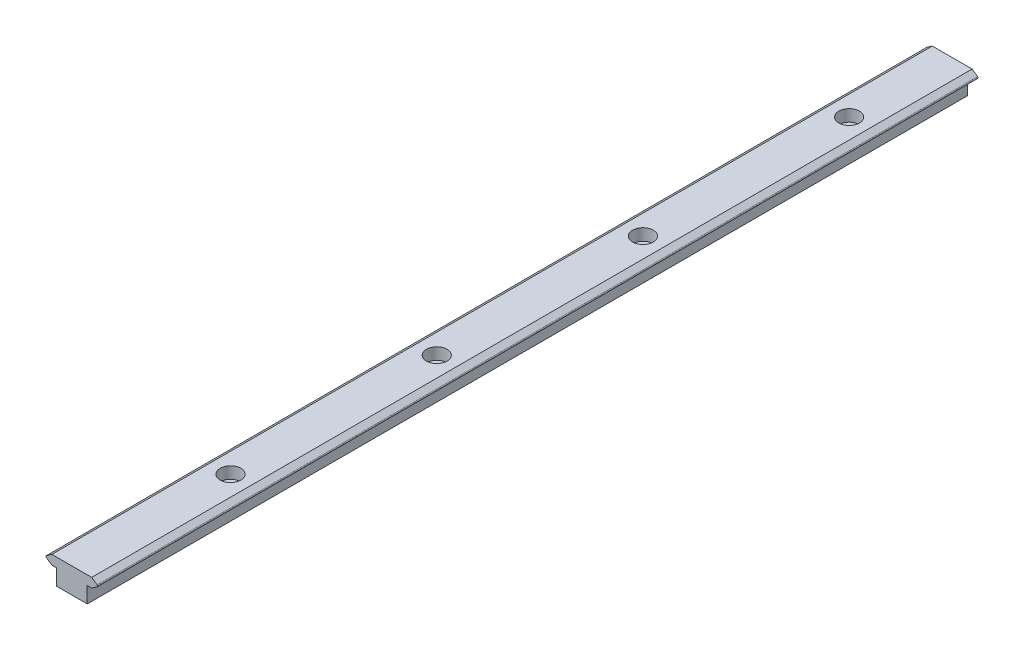
SolidWorks part; units mm, degrees
material "A6061"
ref_plane "前视基准面" through (0, 0, 0) normal (0, 0, 1) x (1, 0, 0)
ref_plane "上视基准面" through (0, 0, 0) normal (0, 1, 0) x (1, 0, 0)
ref_plane "右视基准面" through (0, 0, 0) normal (1, 0, 0) x (0, 0, -1)
sketch "草图1" plane through (0, 0, 0) normal (0, 0, 1) x (1, 0, 0)
  line L0 (185.1567, 2.25) -> (0, 2.25)
  line L1 (0, 2.25) -> (0, -2.25)
  line L2 (0, -2.25) -> (185.1567, -2.25)
  line L3 (185.1567, -2.25) -> (187.7851, -0.4096)
  line L4 (187.7851, 0.4096) -> (185.1567, 2.25)
  line L5 (0, 2.25) -> (0, -2.25) construction
  spline S0 degree 3 poles (187.7851, 0.4096) (187.8309, 0.3775) (187.8718, 0.337) (187.9045, 0.2916) (187.9371, 0.2461) (187.9623, 0.1944) (187.9781, 0.1407) (187.9938, 0.087) (188.0005, 0.0298) (187.9976, -0.0261) (187.9947, -0.082) (187.9821, -0.1381) (187.9608, -0.1899) (187.9396, -0.2417) (187.9091, -0.2905) (187.8719, -0.3323) (187.8461, -0.3612) (187.8168, -0.3874) (187.7851, -0.4096) knots 0 0 0 0 0.000168 0.000168 0.000168 0.000336 0.000336 0.000336 0.000504 0.000504 0.000504 0.000672 0.000672 0.000672 0.000839 0.000839 0.000839 0.000955 0.000955 0.000955 0.000955
revolve "旋转1" add sketch "草图1" angle 360 about L5
sketch "草图2" plane through (0, -2.25, 0) normal (0, -1, 0) x (1, 0, 0)
  circle A0 centre (0, 0) radius 183
extrude "凸台-拉伸1" add sketch "草图2" along normal blind 7.75
sketch "草图3" plane through (0, 0, 0) normal (0, 0, 1) x (1, 0, 0)
  line L0 (165.8433, 2.25) -> (0, 2.25)
  line L1 (0, 2.25) -> (0, -10)
  line L2 (0, -10) -> (168, -10)
  line L3 (168, -10) -> (168, -2.25)
  line L4 (168, -2.25) -> (165.8433, -2.25)
  line L5 (165.8433, -2.25) -> (163.2149, -0.4096)
  line L6 (163.2149, 0.4096) -> (165.8433, 2.25)
  line L7 (0, 2.25) -> (0, -10) construction
  arc A0 (163.2149, -0.4096) -> (163.2149, 0.4096) centre (163.5017, 0) cw
revolve "切除-旋转1" cut sketch "草图3" angle 360 about L7
hole_wizard "M5 六角头螺栓的柱形沉头孔1" positions "草图5" profile "草图4" counterbore size "M5" standard "ANSI Metric"
sketch "草图5" plane through (0, 2.25, 0) normal (0, 1, 0) x (1, 0, 0)
  point P0 (-45.4227, -169.52)
  point P1 (-124.0972, -124.0972)
  point P2 (-169.52, -45.4227)
  point P3 (45.4227, -169.52)
  point P4 (124.0972, -124.0972)
  point P5 (169.52, -45.4227)
  point P6 (-45.4227, 169.52)
  point P7 (-124.0972, 124.0972)
  point P8 (-169.52, 45.4227)
  point P9 (45.4227, 169.52)
  point P10 (124.0972, 124.0972)
  point P11 (169.52, 45.4227)
sketch "草图4" plane through (-45.4227, 2.25, 169.52) normal (1, 0, 0) x (0, 0, 1)
  line L0 (0, 0) -> (0, 12.25)
  line L1 (0, 12.25) -> (2.75, 12.25)
  line L3 (2.75, 12.25) -> (2.75, 6)
  line L4 (2.75, 6) -> (4.5, 6)
  line L5 (4.5, 6) -> (4.5, 0)
  line L7 (4.5, 0) -> (0, 0)
  line L11 (0, -6.35) -> (0, 107.95) construction
  dimension "通孔孔直径" = 5.5
  dimension "通孔孔深度" = 12.25
  dimension "柱形沉头孔直径" = 9
  dimension "柱形沉头孔深度" = 6
sketch "草图6" plane through (0, 2.25, 0) normal (0, 1, 0) x (1, 0, 0)
  line L1 (-255.1095, 0) -> (244.8021, 0)
  line L2 (-255.1095, 0) -> (-255.1095, -215.3522)
  line L3 (-255.1095, -215.3522) -> (244.8021, -215.3522)
  line L4 (244.8021, 0) -> (244.8021, -215.3522)
extrude "切除-拉伸1" cut sketch "草图6" against normal through all
sketch "草图7" plane through (0, 0, 0) normal (0, 0, 1) x (1, 0, 0)
  line L10 (-185.1567, 2.25) -> (-187.7851, 0.4096)
  line L11 (-187.7851, -0.4096) -> (-185.1567, -2.25)
  line L12 (-185.1567, -2.25) -> (-183, -2.25)
  line L13 (-183, -2.25) -> (-183, -10)
  line L14 (-183, -10) -> (-168, -10)
  line L15 (-168, -10) -> (-168, -2.25)
  line L16 (-168, -2.25) -> (-165.8433, -2.25)
  line L17 (-165.8433, -2.25) -> (-163.2149, -0.4096)
  line L18 (-163.2149, 0.4096) -> (-165.8433, 2.25)
  line L19 (-165.8433, 2.25) -> (-185.1567, 2.25)
  line L20 (-185.1567, 2.25) -> (-187.7851, 0.4096)
  line L21 (-187.7851, -0.4096) -> (-185.1567, -2.25)
  line L22 (-185.1567, -2.25) -> (-183, -2.25)
  line L23 (-183, -2.25) -> (-183, -10)
  line L24 (-183, -10) -> (-168, -10)
  line L25 (-168, -10) -> (-168, -2.25)
  line L26 (-168, -2.25) -> (-165.8433, -2.25)
  line L27 (-165.8433, -2.25) -> (-163.2149, -0.4096)
  line L28 (-163.2149, 0.4096) -> (-165.8433, 2.25)
  line L29 (-165.8433, 2.25) -> (-185.1567, 2.25)
  arc A1 (-163.2149, -0.4096) -> (-163.2149, 0.4096) centre (-163.5017, 0) ccw
  arc A2 (-163.2149, -0.4096) -> (-163.2149, 0.4096) centre (-163.5017, 0) ccw
  spline S1 degree 3 poles (-2849.8022, -2983.6595) (-106.9971, -36.1581) (-184.8082, 4.6052) (-187.9045, 0.2916) (-187.9371, 0.2461) (-187.9623, 0.1944) (-187.9781, 0.1407) (-187.9938, 0.087) (-188.0005, 0.0298) (-187.9976, -0.0261) (-187.9947, -0.082) (-187.9821, -0.1381) (-187.9608, -0.1899) (-187.9396, -0.2417) (-187.9091, -0.2905) (-187.8719, -0.3323) (-184.3446, -4.2983) (-113.5783, 45.0295) (-3001.2861, 2841.1379) knots -0.015761 -0.015761 -0.015761 -0.015761 0.000168 0.000168 0.000168 0.000336 0.000336 0.000336 0.000504 0.000504 0.000504 0.000672 0.000672 0.000672 0.000839 0.000839 0.000839 0.016644 0.016644 0.016644 0.016644 only from (-187.7851, 0.4096) to (-187.7851, -0.4096)
  spline S2 degree 3 poles (-187.7851, 0.4096) (-187.8309, 0.3775) (-187.8718, 0.337) (-187.9045, 0.2916) (-187.9371, 0.2461) (-187.9623, 0.1944) (-187.9781, 0.1407) (-187.9938, 0.087) (-188.0005, 0.0298) (-187.9976, -0.0261) (-187.9947, -0.082) (-187.9821, -0.1381) (-187.9608, -0.1899) (-187.9396, -0.2417) (-187.9091, -0.2905) (-187.8719, -0.3323) (-187.8461, -0.3612) (-187.8168, -0.3874) (-187.7851, -0.4096) knots 0 0 0 0 0.000168 0.000168 0.000168 0.000336 0.000336 0.000336 0.000504 0.000504 0.000504 0.000672 0.000672 0.000672 0.000839 0.000839 0.000839 0.000955 0.000955 0.000955 0.000955
  dimension "D1" = 0
extrude "凸台-拉伸2" add sketch "草图7" along normal blind 427
sketch "草图8" plane through (0, 0, 0) normal (0, 0, 1) x (1, 0, 0)
  line L1 (-230.0672, 172.0588) -> (308.8068, 172.0588)
  line L2 (-230.0672, 172.0588) -> (-230.0672, -216.7179)
  line L3 (-230.0672, -216.7179) -> (308.8068, -216.7179)
  line L4 (308.8068, 172.0588) -> (308.8068, -216.7179)
extrude "切除-拉伸2" cut sketch "草图8" against normal through all
sketch "草图9" plane through (0, 2.25, 0) normal (0, 1, 0) x (1, 0, 0)
  line L0 (-175.5, 0) -> (-175.5, -427) construction
  line L1 (-185.1567, 0) -> (-165.8433, 0) construction
  line L2 (-165.8433, -427) -> (-185.1567, -427) construction
  circle A0 centre (-175.5, -50) radius 2.5
  circle A1 centre (-175.5, -150) radius 2.5
  circle A2 centre (-175.5, -250) radius 2.5
  circle A3 centre (-175.5, -350) radius 2.5
  circle A4 centre (-175.5, -450) radius 2.5
  dimension "D1" = 5
  dimension "D2" = 50
  dimension "D3" = 5
hole_wizard "打孔尺寸(%根据)内六角圆柱头螺钉的类型1" positions "草图10" profile "草图11" counterbore size "M5" standard "GB" end condition through all
sketch "草图10" plane through (0, 2.25, 0) normal (0, 1, 0) x (1, 0, 0)
  point P0 (-175.5, -50)
  point P3 (-175.5, -450)
  point P10 (-175.5, -150)
  point P13 (-175.5, -350)
  point P16 (-175.5, -250)
sketch "草图11" plane through (-175.5, 2.25, 50) normal (1, 0, 0) x (0, 0, 1)
  line L0 (0, 0) -> (0, 12.25)
  line L1 (0, 12.25) -> (2.75, 12.25)
  line L3 (2.75, 12.25) -> (2.75, 5.7)
  line L4 (2.75, 5.7) -> (5, 5.7)
  line L5 (5, 5.7) -> (5, 0)
  line L7 (5, 0) -> (0, 0)
  line L11 (0, -6.35) -> (0, 107.95) construction
  dimension "通孔孔直径" = 5.5
  dimension "通孔孔深度" = 12.25
  dimension "柱形沉头孔直径" = 10
  dimension "柱形沉头孔深度" = 5.7
